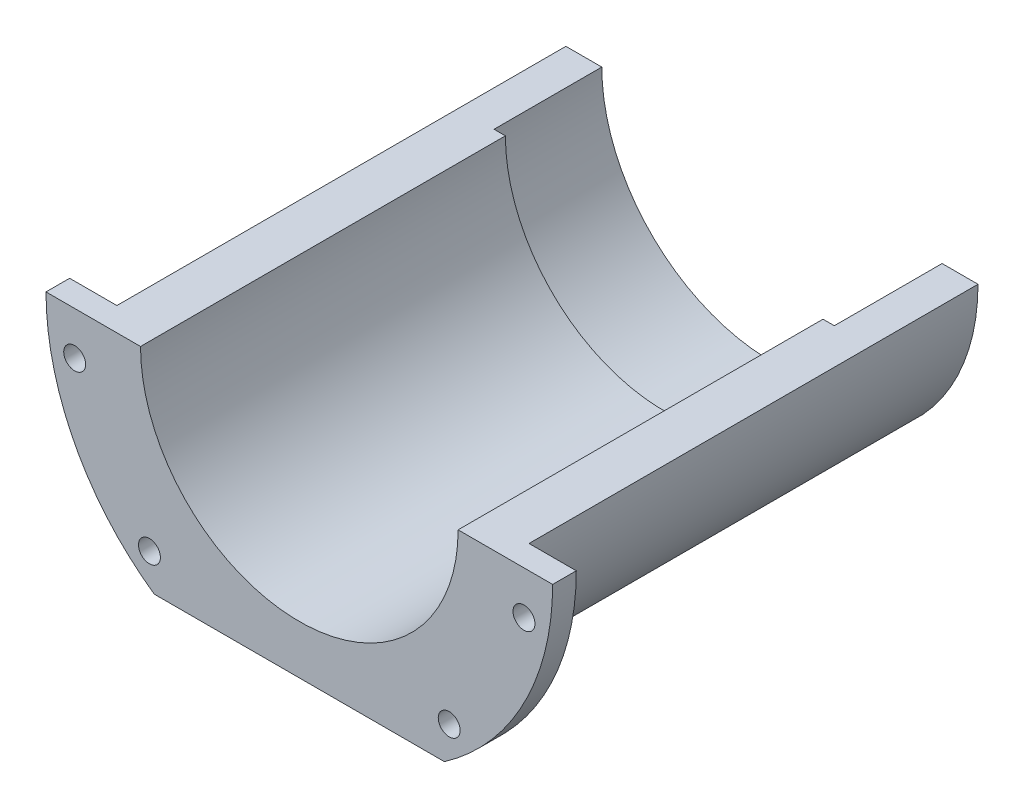
SolidWorks part; units mm, degrees
ref_plane "Front Plane" through (0, 0, 0) normal (0, 0, 1) x (1, 0, 0)
ref_plane "Top Plane" through (0, 0, 0) normal (0, 1, 0) x (1, 0, 0)
ref_plane "Right Plane" through (0, 0, 0) normal (1, 0, 0) x (0, 0, -1)
sketch "Sketch1" plane through (0, 0, 0) normal (0, 0, 1) x (1, 0, 0)
  circle A0 centre (0, 0) radius 21.336
  circle A1 centre (0, 0) radius 27.686
  circle A2 centre (0, 0) radius 40.386
extrude "Boss-Extrude1" add sketch "Sketch1" along normal blind 63.5 contours A1 A0
sketch "Sketch2" plane through (0, 0, 63.5) normal (0, 0, 1) x (1, 0, 0)
  circle A0 centre (0, 0) radius 34.036
  circle A1 centre (0, 0) radius 27.686
  circle A2 centre (0, 0) radius 21.336 construction
extrude "Boss-Extrude2" add sketch "Sketch2" against normal blind 3.175
sketch "Sketch3" plane through (0, 0, 60.325) normal (0, 0, -1) x (-1, 0, 0)
  line L1 (-45.3508, 0) -> (52.3653, 0)
  line L2 (-45.3508, 0) -> (-45.3508, 43.5972)
  line L3 (-45.3508, 43.5972) -> (52.3653, 43.5972)
  line L4 (52.3653, 0) -> (52.3653, 43.5972)
extrude "Cut-Extrude1" cut sketch "Sketch3" along normal blind 101.6 and the other way blind 101.6
sketch "Sketch4" plane through (0, 0, 60.325) normal (0, 0, -1) x (-1, 0, 0)
  circle A0 centre (0, 0) radius 30.7342
  circle A1 centre (-30.1839, -5.7898) radius 1.4732
  circle A2 centre (30.1839, -5.7898) radius 1.4732
  circle A3 centre (-20.1372, -23.2182) radius 1.4732
  circle A4 centre (20.1372, -23.2182) radius 1.4732
  circle A5 centre (0, -30.7342) radius 1.4732
  point P7 (0, 0)
  point P10 (30.382, -4.6392)
  point P13 (0, 0)
  point P16 (0, 0)
  dimension "D1" = 61.4684
  dimension "D2" = 2.9464
  dimension "D3" = 20.1168
  dimension "D5" = 21.4941
extrude "Cut-Extrude2" cut sketch "Sketch4" against normal blind 101.6 contours A0 A1 | A0 A1 | A0 A3 | A0 A3 | A0 A4 | A0 A4 | A0 A2 | A0 A2 | A0 A5 | A0 A5
sketch "Sketch5" plane through (0, 0, 60.325) normal (0, 0, -1) x (-1, 0, 0)
  line L1 (-22.9355, -27.8989) -> (22.5548, -27.8989)
  line L2 (-22.9355, -27.8989) -> (-22.9355, -36.2736)
  line L3 (-22.9355, -36.2736) -> (22.5548, -36.2736)
  line L4 (22.5548, -27.8989) -> (22.5548, -36.2736)
  dimension "D1" = 8.3748
extrude "Cut-Extrude3" cut sketch "Sketch5" against normal blind 101.6
ref_plane "Plane1" through (0, 0, 0) normal (0, 0, -1) x (-1, 0, 0)
sketch "Sketch6" plane through (0, 0, 0) normal (0, 0, -1) x (-1, 0, 0)
  circle A0 centre (0, 0) radius 22.86
extrude "Cut-Extrude4" cut sketch "Sketch6" against normal blind 14.478
